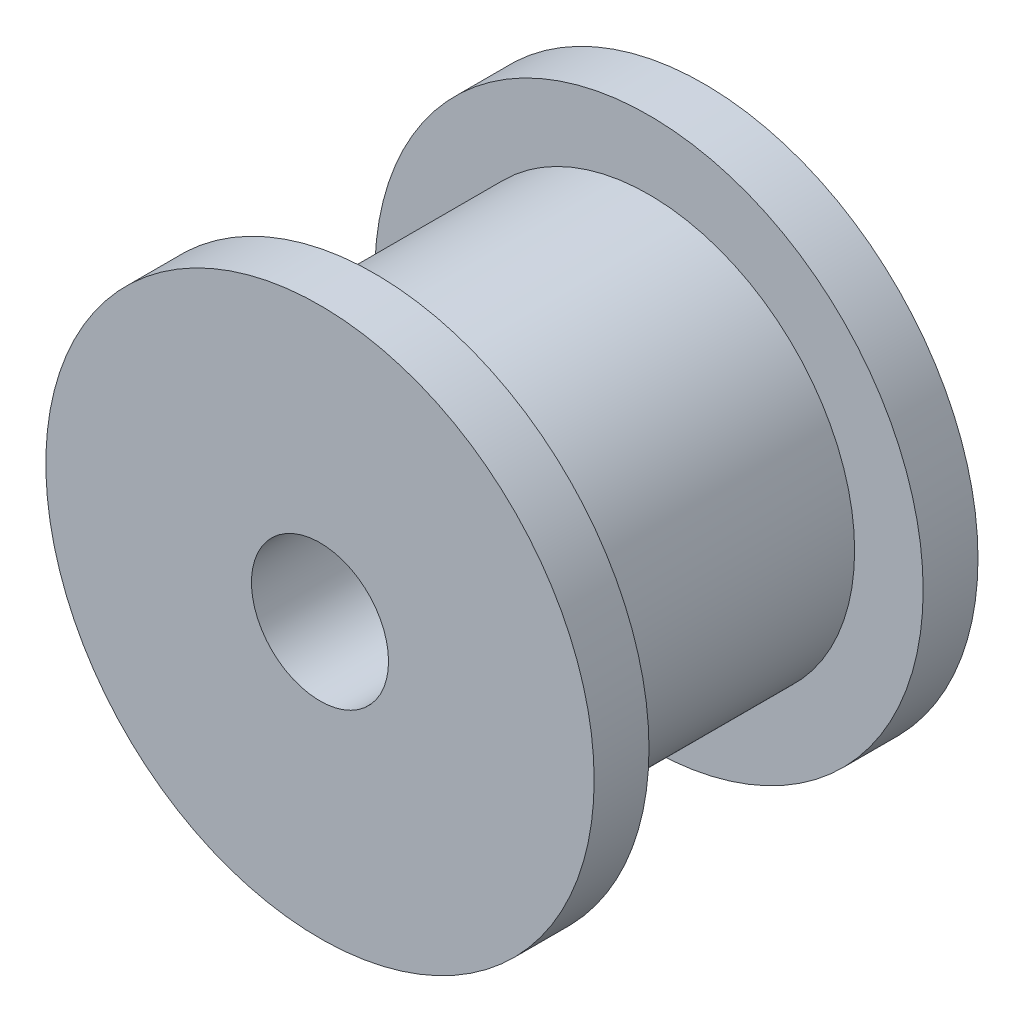
SolidWorks part; units mm, degrees
ref_plane "前视基准面" through (0, 0, 0) normal (0, 0, 1) x (1, 0, 0)
ref_plane "上视基准面" through (0, 0, 0) normal (0, 1, 0) x (1, 0, 0)
ref_plane "右视基准面" through (0, 0, 0) normal (1, 0, 0) x (0, 0, -1)
sketch "Sketch1" plane through (0, 0, 0) normal (0, 0, 1) x (1, 0, 0)
  circle A0 centre (0, 0) radius 10
extrude "Boss-Extrude1" add sketch "Sketch1" along normal mid plane 14
sketch "Sketch2" plane through (0, 0, 0) normal (0, 0, 1) x (1, 0, 0)
  circle A0 centre (0, 0) radius 7.5
  circle A1 centre (0, 0) radius 10
extrude "Cut-Extrude2" cut sketch "Sketch2" against normal mid plane 10
sketch "Sketch3" plane through (0, 0, 7) normal (0, 0, 1) x (1, 0, 0)
  circle A0 centre (0, 0) radius 2.5
extrude "Cut-Extrude3" cut sketch "Sketch3" against normal up to next
